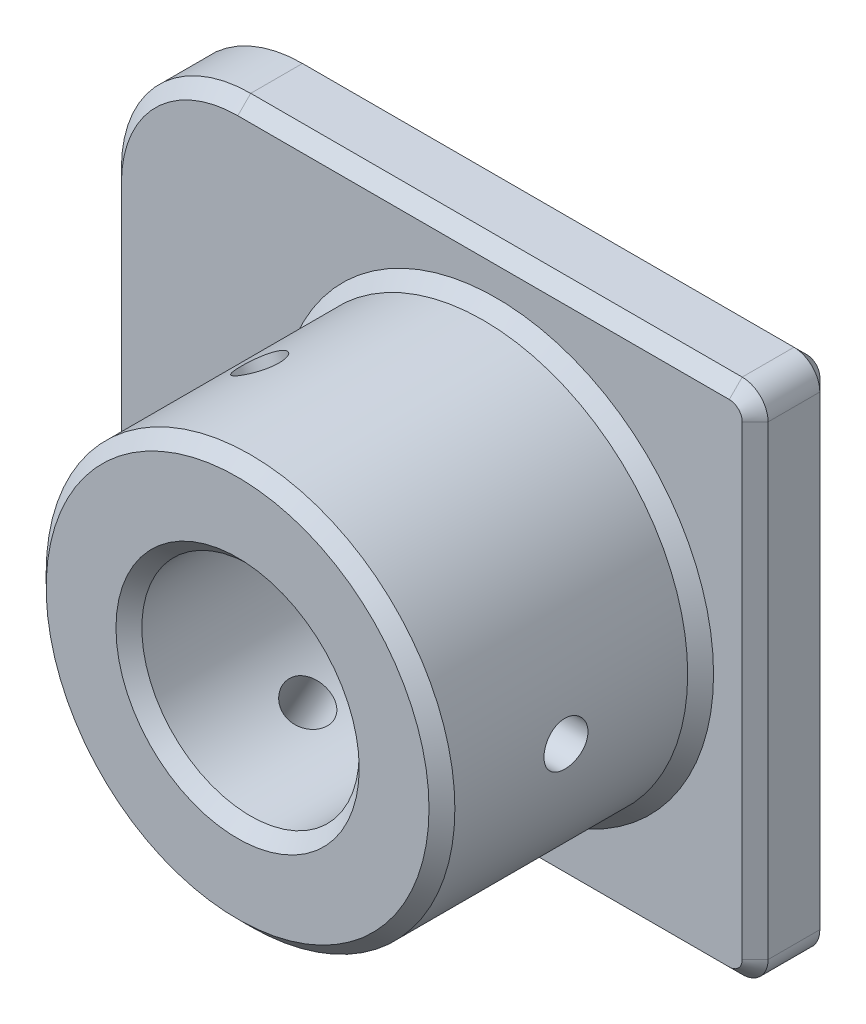
SolidWorks part; units mm, degrees
ref_plane "Front Plane" through (0, 0, 0) normal (0, 0, 1) x (1, 0, 0)
ref_plane "Top Plane" through (0, 0, 0) normal (0, 1, 0) x (1, 0, 0)
ref_plane "Right Plane" through (0, 0, 0) normal (1, 0, 0) x (0, 0, -1)
other "Graphic1"
other "Graphic (Closed) -1"
sketch "Sketch1" plane through (0, 0, 0) normal (0, 0, 1) x (1, 0, 0)
  line L0 (-0.01, -0.0358) -> (0.0182, -0.0358) construction
  line L2 (0.009, -0.0258) -> (-0.01, -0.0258)
  line L3 (0.01, -0.0268) -> (0.01, -0.0448)
  line L4 (0.009, -0.0458) -> (-0.01, -0.0458)
  line L5 (-0.015, -0.0308) -> (-0.015, -0.0408)
  circle A0 centre (0, -0.0358) radius 0.005
  circle A1 centre (0, -0.0358) radius 0.0079
  arc A2 (-0.01, -0.0258) -> (-0.015, -0.0308) centre (-0.01, -0.0308) ccw
  arc A3 (-0.01, -0.0458) -> (-0.015, -0.0408) centre (-0.01, -0.0408) cw
  arc A4 (0.01, -0.0448) -> (0.009, -0.0458) centre (0.009, -0.0448) cw
  arc A5 (0.009, -0.0258) -> (0.01, -0.0268) centre (0.009, -0.0268) cw
  point P9 (0, 0)
  point P14 (-0.015, -0.0458)
  point P17 (0.01, -0.0458)
  dimension "D4" = 0.005
  dimension "D5" = 0.001
  dimension "D6" = 0.0158
  dimension "D7" = 0.01
  dimension "D1" = 0.01
  dimension "D2" = 0.01
  dimension "D3" = 0.025
extrude "Boss-Extrude1" add sketch "Sketch1" along normal blind 0.003
sketch "Sketch2" plane through (0, 0, 0.003) normal (0, 0, 1) x (1, 0, 0)
  circle A0 centre (0, -0.0358) radius 0.0079
  circle A1 centre (0, -0.0358) radius 0.0042
extrude "Boss-Extrude3" add sketch "Sketch2" along normal blind 0.01
chamfer "Chamfer1" distance 0.0005 angle 45 20 edges at (-0.0005, -0.0458, 0) (-0.0005, -0.0458, 0.003) (-0.0135, -0.0443, 0) (-0.0135, -0.0443, 0.003) (-0.015, -0.0358, 0) (-0.015, -0.0358, 0.003) (-0.0135, -0.0273, 0) (-0.0135, -0.0273, 0.003) (-0.0005, -0.0258, 0) (-0.0005, -0.0258, 0.003) (0.0097, -0.0261, 0) (0.0097, -0.0261, 0.003) (0.01, -0.0358, 0) (0.01, -0.0358, 0.003) (0.0097, -0.0455, 0) (0.0097, -0.0455, 0.003) (0.0079, -0.0358, 0.013) (0.0079, -0.0358, 0.003) (0.0042, -0.0358, 0.013) (0.005, -0.0358, 0)
sketch "Sketch3" plane through (0.01, 0, 0) normal (1, 0, 0) x (0, 0, -1)
  line L1 (0, -0.0279) -> (0, -0.0437) construction
  line L2 (0, -0.0358) -> (-0.0191, -0.0358) construction
  circle A0 centre (-0.0082, -0.0358) radius 0.0009
  point P2 (0, 0)
  dimension "D1" = 0.0017
extrude "Cut-Extrude1" cut sketch "Sketch3" against normal up to next and the other way through all
pattern_circular "CirPattern1" count 3 over 360 about axis through (0, -0.0358, 0.0125) along (0, 0, 1) of "Cut-Extrude1"
